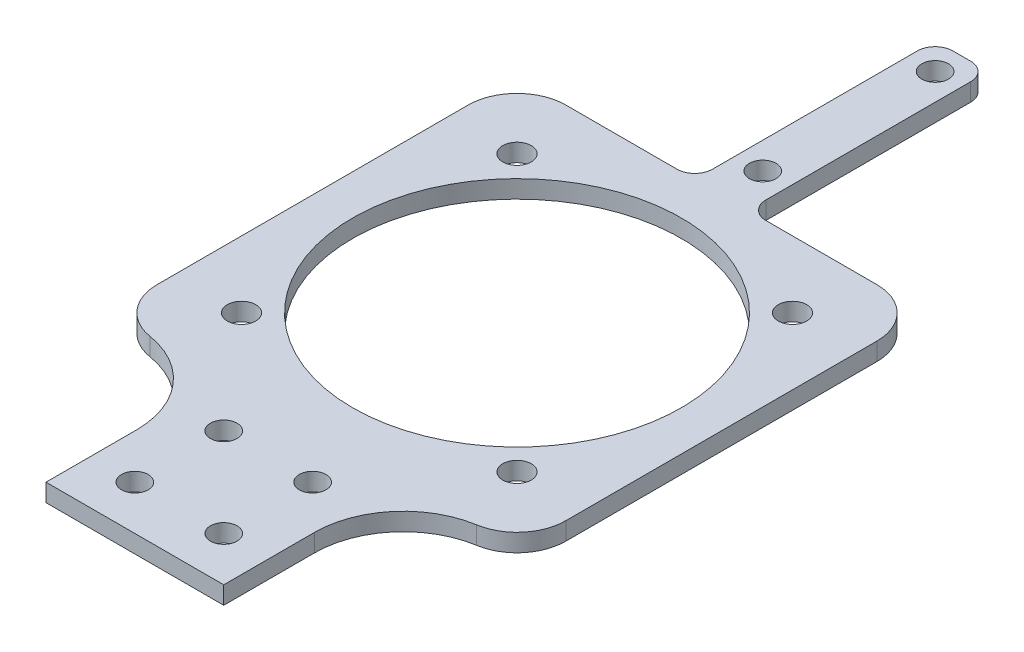
SolidWorks part; units mm, degrees
ref_plane "前视基准面" through (0, 0, 0) normal (0, 0, 1) x (1, 0, 0)
ref_plane "上视基准面" through (0, 0, 0) normal (0, 1, 0) x (1, 0, 0)
ref_plane "右视基准面" through (0, 0, 0) normal (1, 0, 0) x (0, 0, -1)
other "Configuration Table"
sketch "草图2" plane through (0, 0, 0) normal (0, 1, 0) x (1, 0, 0)
  line L1 (-23, -23) -> (23, -23)
  line L2 (-23, -23) -> (-23, 23)
  line L3 (-23, 23) -> (23, 23)
  line L4 (23, -23) -> (23, 23)
  line L5 (-23, -23) -> (23, 23) construction
  line L6 (-23, 23) -> (23, -23) construction
  circle A0 centre (0, 0) radius 18.5
extrude "凸台-拉伸1" add sketch "草图2" along normal blind 2
fillet "圆角1" radius 5.5 4 edges at (23, 1, 23) (23, 1, -23) (-23, 1, -23) (-23, 1, 23)
sketch "草图3" plane through (0, 2, 0) normal (0, 1, 0) x (1, 0, 0)
  line L1 (-15.5, -15.5) -> (15.5, -15.5)
  line L2 (-15.5, -15.5) -> (-15.5, 15.5)
  line L3 (-15.5, 15.5) -> (15.5, 15.5)
  line L4 (15.5, -15.5) -> (15.5, 15.5)
  line L5 (-15.5, -15.5) -> (15.5, 15.5) construction
  line L6 (-15.5, 15.5) -> (15.5, -15.5) construction
  circle A0 centre (-15.5, 15.5) radius 1.6
  circle A1 centre (15.5, 15.5) radius 1.6
  circle A2 centre (-15.5, -15.5) radius 1.6
  circle A3 centre (15.5, -15.5) radius 1.6
  point P0 (0, 0)
extrude "切除-拉伸1" cut sketch "草图3" against normal through all contours A2 | A0 | A1 | A3
sketch "草图4" plane through (0, 2, 0) normal (0, 1, 0) x (1, 0, 0)
  line L0 (-10, -23) -> (-10, -43)
  line L1 (-10, -23) -> (10, -23)
  line L2 (-10, -43) -> (10, -43)
  line L3 (10, -23) -> (10, -43)
  line L4 (-17.5, -23) -> (17.5, -23) construction
  circle A0 centre (-5, -38) radius 1.5
  circle A1 centre (5, -38) radius 1.5
  circle A2 centre (-5, -28) radius 1.5
  circle A3 centre (5, -28) radius 1.5
extrude "凸台-拉伸2" add sketch "草图4" against normal blind 2
sketch "草图5" plane through (0, 2, 0) normal (0, 1, 0) x (1, 0, 0)
  line L13 (-3, 50.05) -> (3, 50.05)
  line L15 (3, 50.05) -> (3, 22.65)
  line L16 (3, 22.65) -> (-3, 22.65)
  line L17 (-3, 50.05) -> (-3, 22.65)
  circle A1 centre (0, 47.05) radius 1.5
  circle A3 centre (0, 27.65) radius 1.5
extrude "凸台-拉伸3" add sketch "草图5" against normal blind 2
fillet "圆角5" radius 2 4 edges at (3, 1, -23) (-3, 1, -23) (3, 1, -50.05) (-3, 1, -50.05)
fillet "圆角6" radius 10 2 edges at (10, 1, 23) (-10, 1, 23)
